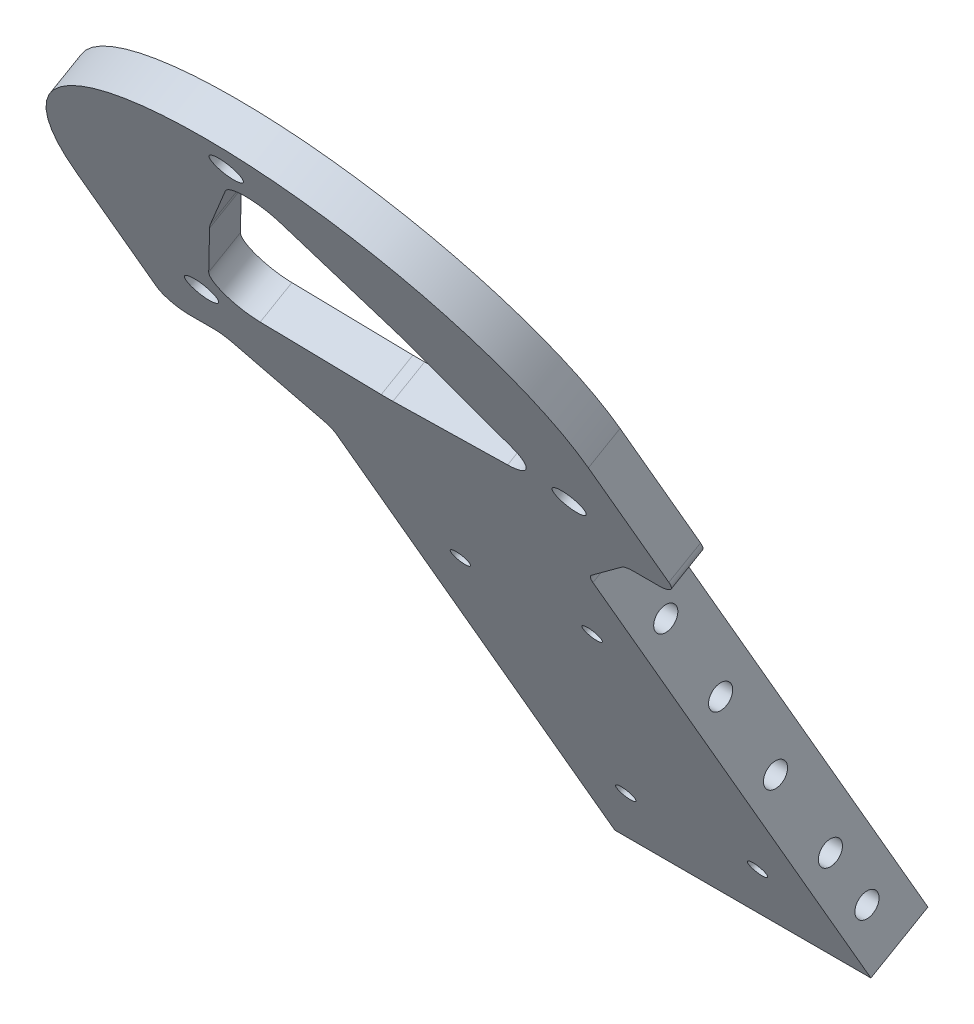
SolidWorks part; units mm, degrees
material "POM 乙缩醛共聚物"
ref_plane "前视基准面" through (0, 0, 0) normal (0, 0, 1) x (1, 0, 0)
ref_plane "上视基准面" through (0, 0, 0) normal (0, 1, 0) x (1, 0, 0)
ref_plane "右视基准面" through (0, 0, 0) normal (1, 0, 0) x (0, 0, -1)
sketch "草图1" plane through (0, 0, 0) normal (0, 0, 1) x (1, 0, 0)
  line L1 (17.5, -5) -> (-17.5, -5)
  line L2 (17.5, -5) -> (17.5, 5)
  line L3 (17.5, 5) -> (-17.5, 5)
  line L4 (-17.5, -5) -> (-17.5, 5)
  line L5 (17.5, -5) -> (-17.5, 5) construction
  line L6 (17.5, 5) -> (-17.5, -5) construction
  point P0 (0, 0)
  dimension "D1" = 10
  dimension "D2" = 35
extrude "凸台-拉伸1" add sketch "草图1" along normal blind 30
sketch "草图2" plane through (17.5, 0, 0) normal (1, 0, 0) x (0, 0, -1)
  line L0 (-30, -5) -> (-30, 5) construction
  circle A0 centre (-26, 0) radius 1.65
  circle A1 centre (-4, 0) radius 1.65
  dimension "D1" = 3.3
  dimension "D2" = 3.3
  dimension "D3" = 4
  dimension "D4" = 22
extrude "切除-拉伸1" cut sketch "草图2" against normal through all
sketch "草图3" plane through (0, 0, 30) normal (0, 0, 1) x (1, 0, 0)
  line L4 (-17.5, 5) -> (-17.5, -5)
  line L5 (-17.5, -5) -> (17.5, -5)
  line L6 (17.5, -5) -> (17.5, 5)
  line L7 (17.5, 5) -> (-17.5, 5)
  line L8 (-17.5, 5) -> (-17.5, -5)
  line L9 (-17.5, -5) -> (17.5, -5)
  line L10 (17.5, -5) -> (17.5, 5)
  line L11 (17.5, 5) -> (-17.5, 5)
  dimension "D1" = 0
sketch "草图4" plane through (0, 0, 0) normal (1, 0, 0) x (0, 0, -1)
  line L0 (-30, 0) -> (-31.1132, 0)
  line L1 (-30, 5) -> (-30, -5) construction
  line L2 (-35.4434, 2.5) -> (-99, 112.5833)
  arc A0 (-31.1132, 0) -> (-35.4434, 2.5) centre (-31.1132, 5) cw
  point P8 (-34, 0)
  dimension "D4" = 5
  dimension "D1" = 4
  dimension "D2" = 120
  dimension "D3" = 130
sweep "扫描3" add profiles "草图3" path "草图4"
fillet "圆角1" radius 5 1 edges at (0, 5, 31.1132)
sketch "草图6" plane through (0, -12.2224, 21.1699) normal (0, 0.5, -0.866) x (-1, 0, 0)
  line L0 (-17.5, 147) -> (17.5, 147) construction
  line L1 (35, 87) -> (-35, 87)
  line L2 (35, 87) -> (35, 147)
  line L3 (35, 147) -> (-35, 147)
  line L4 (-35, 87) -> (-35, 147)
  line L5 (35, 87) -> (-35, 147) construction
  line L6 (35, 147) -> (-35, 87) construction
  point P0 (0, 117)
  dimension "D1" = 60
  dimension "D2" = 70
extrude "凸台-拉伸2" add sketch "草图6" against normal up to surface (10 mm away) contours L2 L1 L4 L3 up to face at (0, 55.0417, 71.5518)
chamfer "倒角1" distance 10 angle 45 2 edges at (-17.5, 60.6218, 69) (17.5, 60.6218, 69)
sketch "草图7" plane through (0, -12.2224, 21.1699) normal (0, 0.5, -0.866) x (-1, 0, 0)
  line L1 (35, 87) -> (35, 147) construction
  line L2 (-35, 147) -> (35, 147) construction
  line L3 (-35, 87) -> (-35, 147) construction
  line L4 (-35, 112) -> (-35, 147)
  line L5 (-35, 147) -> (35, 147)
  line L6 (35, 147) -> (35, 112)
  circle A0 centre (0, 112) radius 35
  line M2 (35, 147) -> (-35, 147)
  line M3 (-35, 147) -> (-35, 87)
  line M11 (35, 87) -> (35, 147)
extrude "切除-拉伸3" cut sketch "草图7" against normal blind 15 contours A0 L5 M3 | A0 M11 M2
sketch "草图8" plane through (0, -12.2224, 21.1699) normal (0, 0.5, -0.866) x (-1, 0, 0)
  circle A0 centre (0, 112) radius 15
  dimension "D1" = 30
extrude "切除-拉伸4" cut sketch "草图8" against normal blind 15
sketch "草图10" plane through (0, -12.2224, 21.1699) normal (0, 0.5, -0.866) x (-1, 0, 0)
  line L1 (0, 141) -> (-25.1147, 97.5) construction
  line L2 (-25.1147, 97.5) -> (25.1147, 97.5) construction
  line L3 (25.1147, 97.5) -> (0, 141) construction
  circle A0 centre (0, 112) radius 14.5 construction
  circle A1 centre (0, 141) radius 2.1
  circle A2 centre (-25.1147, 97.5) radius 2.1
  circle A3 centre (25.1147, 97.5) radius 2.1
  dimension "D2" = 4.2
  dimension "D3" = 4.2
  dimension "D4" = 4.2
  dimension "D1" = 29
extrude "切除-拉伸6" cut sketch "草图10" against normal through all
sketch "草图11" plane through (0, -12.2224, 21.1699) normal (0, 0.5, -0.866) x (-1, 0, 0)
  line L0 (-25.1147, 97.5) -> (0, 112) construction
  line L1 (0, 127) -> (0, 97) construction
  circle A0 centre (-16.671, 102.375) radius 4.5
  circle A1 centre (0, 112) radius 15 construction
  circle A2 centre (16.671, 102.375) radius 4.5
  dimension "D1" = 9
  dimension "D2" = 19.25
extrude "切除-拉伸7" cut sketch "草图11" against normal through all
sketch "草图12" plane through (0, -12.2224, 21.1699) normal (0, 0.5, -0.866) x (-1, 0, 0)
  line L0 (-20.6825, 104.4141) -> (-13.3717, 118.7969)
  line L1 (13.3717, 118.7969) -> (20.6825, 104.4141)
  line L2 (-0.7996, 97.0213) -> (-16.9109, 97.8814)
  line L3 (-13.3717, 118.7969) -> (-20.6825, 104.4141)
  line L4 (-16.9109, 97.8814) -> (-0.7996, 97.0213)
  line L5 (0.7996, 97.0213) -> (16.9109, 97.8814)
  line L6 (-12.5721, 120.1818) -> (-3.7716, 133.7045)
  line L7 (12.5721, 120.1818) -> (3.7716, 133.7045)
  arc A0 (12.289, 103.3988) -> (13.5933, 105.658) centre (16.671, 102.375) ccw construction
  arc A1 (-13.5933, 105.658) -> (-12.289, 103.3988) centre (-16.671, 102.375) ccw construction
  arc A2 (-12.289, 103.3988) -> (12.289, 103.3988) centre (0, 112) ccw construction
  arc A3 (13.5933, 105.658) -> (-13.5933, 105.658) centre (0, 112) ccw construction
  arc A4 (16.9109, 97.8814) -> (20.6825, 104.4141) centre (16.671, 102.375) ccw
  arc A5 (-20.6825, 104.4141) -> (-16.9109, 97.8814) centre (-16.671, 102.375) ccw
  arc A6 (-0.7996, 97.0213) -> (0.7996, 97.0213) centre (0, 112) ccw
  arc A7 (13.3717, 118.7969) -> (12.5721, 120.1818) centre (0, 112) ccw
  arc A8 (-20.6825, 104.4141) -> (-16.9109, 97.8814) centre (-16.671, 102.375) ccw
  arc A9 (3.7716, 133.7045) -> (-3.7716, 133.7045) centre (0, 131.25) ccw
  arc A10 (-12.5721, 120.1818) -> (-13.3717, 118.7969) centre (0, 112) ccw
  point P28 (0, 112)
  dimension "D1" = 3
sketch "草图14" plane through (0, -12.2224, 21.1699) normal (0, 0.5, -0.866) x (-1, 0, 0)
  line L1 (-17.5, 22.7735) -> (17.5, 22.7735)
  line L2 (-17.5, 22.7735) -> (-17.5, -4.3301)
  line L3 (-17.5, -4.3301) -> (17.5, -4.3301)
  line L4 (17.5, 22.7735) -> (17.5, -4.3301)
extrude "切除-拉伸12" cut sketch "草图12" against normal blind 25 contours L6 A9 L7 A7 L1 A4 L5 A6 L4 A5 L0 A10
extrude "切除-拉伸10" cut sketch "草图14" against normal through all both and the other way through all
sketch "草图15" plane through (0, 19.7224, 11.3868) normal (0, -0.866, -0.5) x (1, 0, 0)
  line L4 (17.5, 34.4449) -> (-17.5, 34.4449)
  line L5 (-17.5, 34.4449) -> (-17.5, 24.4449)
  line L6 (-17.5, 24.4449) -> (17.5, 24.4449)
  line L7 (17.5, 24.4449) -> (17.5, 34.4449)
  line L8 (17.5, 34.4449) -> (-17.5, 34.4449)
  line L9 (-17.5, 34.4449) -> (-17.5, 24.4449)
  line L10 (-17.5, 24.4449) -> (17.5, 24.4449)
  line L11 (17.5, 24.4449) -> (17.5, 34.4449)
  dimension "D1" = 0
extrude "凸台-拉伸3" add sketch "草图15" along normal blind 23
sketch "草图16" plane through (17.5, 0, 0) normal (1, 0, 0) x (0, 0, -1)
  line L0 (-34.3868, 0.6699) -> (-29.3868, -7.9904) construction
  line L1 (-29.7169, -17.4186) -> (-68.3301, 49.4615) construction
  line L2 (-21.0566, -12.4186) -> (-29.7169, -17.4186) construction
  line L3 (-21.0566, -12.4186) -> (-59.6699, 54.4615) construction
  circle A0 centre (-29.3868, -7.9904) radius 1.65
  circle A1 centre (-34.3868, 0.6699) radius 1.65
  dimension "D1" = 3.3
  dimension "D2" = 3.3
  dimension "D4" = 8
  dimension "D3" = 10
  dimension "D5" = 5
extrude "切除-拉伸11" cut sketch "草图16" against normal through all both and the other way through all
fillet "圆角2" radius 3 6 edges at (-17.5, 51.9615, 64) (-27.5, 60.6218, 69) (-35, 60.6218, 69) (17.5, 51.9615, 64) (27.5, 60.6218, 69) (35, 60.6218, 69)
sketch "草图18" plane through (0, -12.2224, 21.1699) normal (0, 0.5, -0.866) x (-1, 0, 0)
  line L0 (-17.5, 75.7574) -> (17.5, 75.7574)
  line L9 (28.7426, 87) -> (32, 87)
  line L10 (35, 90) -> (35, 112)
  line L11 (-35, 112) -> (-35, 90)
  line L12 (-32, 87) -> (-28.7426, 87)
  line L13 (-26.6213, 86.1213) -> (-18.3787, 77.8787)
  line L14 (-17.5, 75.7574) -> (-17.5, -0.2265)
  line L15 (-17.5, -0.2265) -> (17.5, -0.2265)
  line L16 (17.5, -0.2265) -> (17.5, 75.7574)
  line L17 (18.3787, 77.8787) -> (26.6213, 86.1213)
  line L18 (28.7426, 87) -> (32, 87)
  line L19 (35, 90) -> (35, 112)
  line L20 (-35, 112) -> (-35, 90)
  line L21 (-32, 87) -> (-28.7426, 87)
  line L22 (-26.6213, 86.1213) -> (-18.3787, 77.8787)
  line L26 (18.3787, 77.8787) -> (26.6213, 86.1213)
  arc A8 (32, 87) -> (35, 90) centre (32, 90) ccw
  arc A9 (35, 112) -> (-35, 112) centre (0, 112) ccw
  arc A10 (-35, 90) -> (-32, 87) centre (-32, 90) ccw
  arc A11 (-26.6213, 86.1213) -> (-28.7426, 87) centre (-28.7426, 84) ccw
  arc A12 (-17.5, 75.7574) -> (-18.3787, 77.8787) centre (-20.5, 75.7574) ccw
  arc A13 (18.3787, 77.8787) -> (17.5, 75.7574) centre (20.5, 75.7574) ccw
  arc A14 (28.7426, 87) -> (26.6213, 86.1213) centre (28.7426, 84) ccw
  arc A15 (32, 87) -> (35, 90) centre (32, 90) ccw
  arc A16 (35, 112) -> (-35, 112) centre (0, 112) ccw
  arc A17 (-35, 90) -> (-32, 87) centre (-32, 90) ccw
  arc A18 (-26.6213, 86.1213) -> (-28.7426, 87) centre (-28.7426, 84) ccw
  arc A19 (-17.5, 75.7574) -> (-18.3787, 77.8787) centre (-20.5, 75.7574) ccw
  arc A20 (18.3787, 77.8787) -> (17.5, 75.7574) centre (20.5, 75.7574) ccw
  arc A21 (28.7426, 87) -> (26.6213, 86.1213) centre (28.7426, 84) ccw
  dimension "D1" = 0
extrude "切除-拉伸13" cut sketch "草图18" against normal blind 4
sketch "草图19" plane through (0, -12.2224, 21.1699) normal (0, 0.5, -0.866) x (-1, 0, 0)
  line L1 (17.5, -0.2265) -> (-17.5, -0.2265)
  line L2 (17.5, -0.2265) -> (17.5, 23.7735)
  line L3 (17.5, 23.7735) -> (-17.5, 23.7735)
  line L4 (-17.5, -0.2265) -> (-17.5, 23.7735)
  dimension "D1" = 24
  dimension "D2" = 35
extrude "凸台-拉伸4" add sketch "草图19" along normal blind 6
sketch "草图20" plane through (-17.5, 0, 0) normal (-1, 0, 0) x (0, 0, 1)
  line L0 (34.3868, 0.6699) -> (29.3868, -7.9904) construction
  line L1 (31.8868, -3.6603) -> (9.2173, 9.4279) construction
  line L2 (22.4585, -3.9904) -> (29.3868, -7.9904) construction
  line L3 (27.4585, 4.6699) -> (34.3868, 0.6699) construction
  circle A0 centre (29.3868, -7.9904) radius 1.65 construction
  circle A1 centre (34.3868, 0.6699) radius 1.65 construction
  circle A2 centre (29.3868, -7.9904) radius 1.65
  circle A3 centre (34.3868, 0.6699) radius 1.65
  circle A4 centre (22.4585, -3.9904) radius 1.65
  circle A5 centre (27.4585, 4.6699) radius 1.65
  dimension "D1" = 3.3
  dimension "D2" = 3.3
  dimension "D3" = 8
  dimension "D4" = 8
extrude "切除-拉伸14" cut sketch "草图20" against normal through all both and the other way through all
sketch "草图21" plane through (0, -17.2224, 29.8301) normal (0, -0.5, 0.866) x (1, 0, 0)
  line L9 (-35, 112) -> (-35, 90)
  line L10 (-32, 87) -> (-28.7426, 87)
  line L11 (-26.6213, 86.1213) -> (-18.3787, 77.8787)
  line L12 (-17.5, 75.7574) -> (-17.5, -0.2265)
  line L13 (-17.5, -0.2265) -> (17.5, -0.2265)
  line L14 (17.5, -0.2265) -> (17.5, 75.7574)
  line L15 (18.3787, 77.8787) -> (26.6213, 86.1213)
  line L16 (28.7426, 87) -> (32, 87)
  line L17 (35, 90) -> (35, 112)
  line L18 (-35, 112) -> (-35, 90)
  line L19 (-32, 87) -> (-28.7426, 87)
  line L20 (-26.6213, 86.1213) -> (-18.3787, 77.8787)
  line L21 (-17.5, 75.7574) -> (-17.5, -0.2265)
  line L22 (-17.5, -0.2265) -> (17.5, -0.2265)
  line L23 (17.5, -0.2265) -> (17.5, 75.7574)
  line L24 (18.3787, 77.8787) -> (26.6213, 86.1213)
  line L25 (28.7426, 87) -> (32, 87)
  line L26 (35, 90) -> (35, 112)
  arc A7 (-35, 90) -> (-32, 87) centre (-32, 90) ccw
  arc A8 (-26.6213, 86.1213) -> (-28.7426, 87) centre (-28.7426, 84) ccw
  arc A9 (-17.5, 75.7574) -> (-18.3787, 77.8787) centre (-20.5, 75.7574) ccw
  arc A10 (18.3787, 77.8787) -> (17.5, 75.7574) centre (20.5, 75.7574) ccw
  arc A11 (28.7426, 87) -> (26.6213, 86.1213) centre (28.7426, 84) ccw
  arc A12 (32, 87) -> (35, 90) centre (32, 90) ccw
  arc A13 (35, 112) -> (-35, 112) centre (0, 112) ccw
  arc A14 (-35, 90) -> (-32, 87) centre (-32, 90) ccw
  arc A15 (-26.6213, 86.1213) -> (-28.7426, 87) centre (-28.7426, 84) ccw
  arc A16 (-17.5, 75.7574) -> (-18.3787, 77.8787) centre (-20.5, 75.7574) ccw
  arc A17 (18.3787, 77.8787) -> (17.5, 75.7574) centre (20.5, 75.7574) ccw
  arc A18 (28.7426, 87) -> (26.6213, 86.1213) centre (28.7426, 84) ccw
  arc A19 (32, 87) -> (35, 90) centre (32, 90) ccw
  arc A20 (35, 112) -> (-35, 112) centre (0, 112) ccw
  dimension "D1" = 0
extrude "切除-拉伸15" cut sketch "草图21" against normal blind 1
sketch "草图22" plane through (-17.5, 0, 0) normal (-1, 0, 0) x (0, 0, 1)
  line L0 (34.3868, 0.6699) -> (49.3868, 26.6506) construction
  line L1 (66.8428, 48.8854) -> (28.8509, -16.9186) construction
  circle A0 centre (49.3868, 26.6506) radius 1.65
  circle A1 centre (56.8868, 39.641) radius 1.65
  circle A2 centre (41.8868, 13.6603) radius 1.65
  dimension "D1" = 3.3
  dimension "D3" = 3.3
  dimension "D4" = 15
  dimension "D5" = 3.3
  dimension "D6" = 15
  dimension "D2" = 30
extrude "切除-拉伸16" cut sketch "草图22" against normal through all
sketch "草图23" plane through (17.5, 0, 0) normal (1, 0, 0) x (0, 0, -1)
  line L0 (-59.0486, 53.3854) -> (-21.0566, -12.4186)
  line L1 (-15.8605, -9.4186) -> (-28.8509, -16.9186) construction
  line L2 (-21.0566, -12.4186) -> (-8.944, -5.4254)
  line L3 (-8.944, -5.4254) -> (-59.0486, 53.3854)
extrude "切除-拉伸17" cut sketch "草图23" against normal through all both and the other way through all
sketch "草图25" plane through (0, -12.2224, 21.1699) normal (0, 0.5, -0.866) x (-1, 0, 0)
  line L3 (17.5, -0.2265) -> (-17.5, -0.2265) construction
  circle A0 centre (-9, 58.9735) radius 1.25
  circle A1 centre (9, 58.9735) radius 1.25
  circle A2 centre (-9, 13.7735) radius 1.25
  circle A3 centre (9, 13.7735) radius 1.25
  dimension "D1" = 2.5
  dimension "D2" = 2.5
  dimension "D3" = 2.5
  dimension "D4" = 2.5
  dimension "D5" = 18
  dimension "D6" = 9
  dimension "D8" = 45.2
  dimension "D9" = 14
extrude "切除-拉伸18" cut sketch "草图25" against normal blind 10
